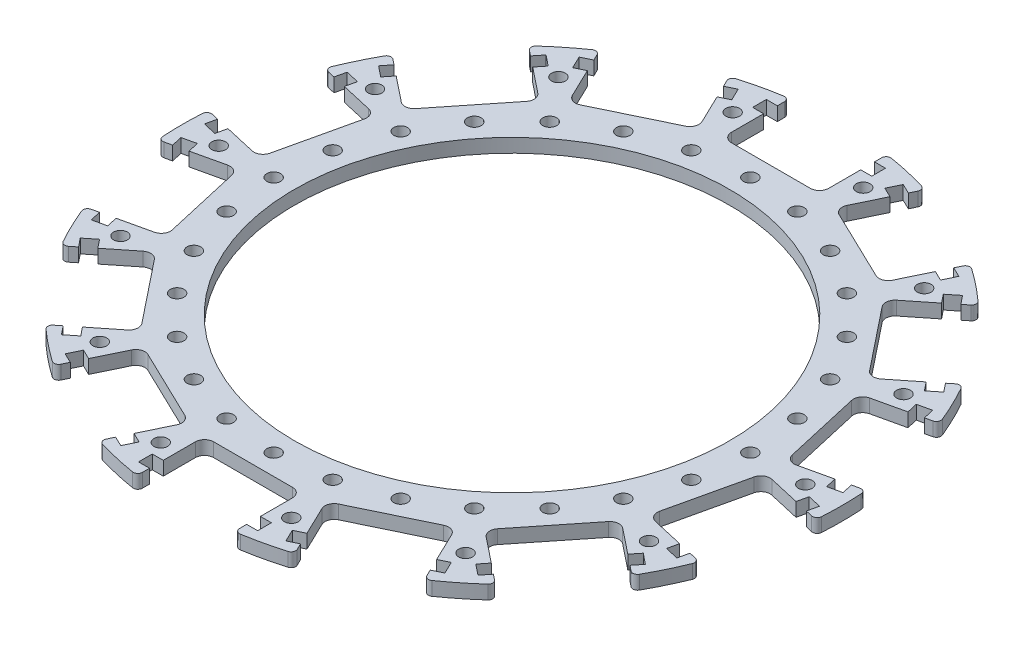
SolidWorks part; units mm, degrees
material "Thornel Mat VMA"
ref_plane "前视基准面" through (0, 0, 0) normal (0, 0, 1) x (1, 0, 0)
ref_plane "上视基准面" through (0, 0, 0) normal (0, 1, 0) x (1, 0, 0)
ref_plane "右视基准面" through (0, 0, 0) normal (1, 0, 0) x (0, 0, -1)
sketch "草图1" plane through (0, 0, 0) normal (0, 1, 0) x (1, 0, 0)
  line L0 (0, 0) -> (0, -67) construction
  line L1 (13, -67) -> (-13, -67) construction
  line L2 (-13, -68.5) -> (-13, -65.5)
  line L3 (0, -67) -> (0, -69.5129) construction
  line L4 (-10.1, -69.5129) -> (10.1, -69.5129) construction
  line L5 (-13, -68.5) -> (-10.6, -68.5)
  line L6 (-10.6, -68.5) -> (-10.6, -71.2154)
  line L7 (-13, -65.5) -> (-10.6, -65.5)
  line L8 (-10.6, -65.5) -> (-10.6, -56.5)
  line L9 (-10.6, -56.5) -> (10.6, -56.5)
  line L10 (10.6, -68.5) -> (10.6, -71.2154)
  line L11 (13, -68.5) -> (10.6, -68.5)
  line L12 (13, -68.5) -> (13, -65.5)
  line L13 (13, -65.5) -> (10.6, -65.5)
  line L14 (10.6, -65.5) -> (10.6, -56.5)
  line L15 (-34.0647, -46.3056) -> (-14.9642, -55.5039)
  line L16 (-37.9697, -54.4143) -> (-34.0647, -46.3056)
  line L17 (-40.132, -53.373) -> (-37.9697, -54.4143)
  line L18 (-41.4336, -56.0759) -> (-40.132, -53.373)
  line L19 (-41.4336, -56.0759) -> (-39.2713, -57.1172)
  line L20 (-39.2713, -57.1172) -> (-40.4495, -59.5637)
  line L21 (-20.1708, -66.3155) -> (-21.349, -68.7621)
  line L22 (-18.0084, -67.3569) -> (-20.1708, -66.3155)
  line L23 (-18.0084, -67.3569) -> (-16.7068, -64.6539)
  line L24 (-16.7068, -64.6539) -> (-18.8691, -63.6126)
  line L25 (-18.8691, -63.6126) -> (-14.9642, -55.5039)
  line L26 (-50.7825, -26.9398) -> (-37.5645, -43.5146)
  line L27 (-57.819, -32.5512) -> (-50.7825, -26.9398)
  line L28 (-59.3153, -30.6748) -> (-57.819, -32.5512)
  line L29 (-61.6608, -32.5452) -> (-59.3153, -30.6748)
  line L30 (-61.6608, -32.5452) -> (-60.1644, -34.4216)
  line L31 (-60.1644, -34.4216) -> (-62.2875, -36.1147)
  line L32 (-46.9465, -50.9965) -> (-49.0695, -52.6895)
  line L33 (-45.4501, -52.8729) -> (-46.9465, -50.9965)
  line L34 (-45.4501, -52.8729) -> (-43.1046, -51.0024)
  line L35 (-43.1046, -51.0024) -> (-44.601, -49.126)
  line L36 (-44.601, -49.126) -> (-37.5645, -43.5146)
  line L37 (-57.4421, -2.2382) -> (-52.7247, -22.9067)
  line L38 (-66.2165, -4.2409) -> (-57.4421, -2.2382)
  line L39 (-66.7506, -1.9011) -> (-66.2165, -4.2409)
  line L40 (-69.6753, -2.5686) -> (-66.7506, -1.9011)
  line L41 (-69.6753, -2.5686) -> (-69.1413, -4.9084)
  line L42 (-69.1413, -4.9084) -> (-71.7886, -5.5127)
  line L43 (-64.4238, -25.5769) -> (-67.0712, -26.1812)
  line L44 (-63.8898, -27.9167) -> (-64.4238, -25.5769)
  line L45 (-63.8898, -27.9167) -> (-60.965, -27.2492)
  line L46 (-60.965, -27.2492) -> (-61.4991, -24.9094)
  line L47 (-61.4991, -24.9094) -> (-52.7247, -22.9067)
  line L48 (-52.7247, 22.9067) -> (-57.4421, 2.2382)
  line L49 (-61.4991, 24.9094) -> (-52.7247, 22.9067)
  line L50 (-60.965, 27.2492) -> (-61.4991, 24.9094)
  line L51 (-63.8898, 27.9167) -> (-60.965, 27.2492)
  line L52 (-63.8898, 27.9167) -> (-64.4238, 25.5769)
  line L53 (-64.4238, 25.5769) -> (-67.0712, 26.1812)
  line L54 (-69.1413, 4.9084) -> (-71.7886, 5.5127)
  line L55 (-69.6753, 2.5686) -> (-69.1413, 4.9084)
  line L56 (-69.6753, 2.5686) -> (-66.7506, 1.9011)
  line L57 (-66.7506, 1.9011) -> (-66.2165, 4.2409)
  line L58 (-66.2165, 4.2409) -> (-57.4421, 2.2382)
  line L59 (-37.5645, 43.5146) -> (-50.7825, 26.9398)
  line L60 (-44.601, 49.126) -> (-37.5645, 43.5146)
  line L61 (-43.1046, 51.0024) -> (-44.601, 49.126)
  line L62 (-45.4501, 52.8729) -> (-43.1046, 51.0024)
  line L63 (-45.4501, 52.8729) -> (-46.9465, 50.9965)
  line L64 (-46.9465, 50.9965) -> (-49.0695, 52.6895)
  line L65 (-60.1644, 34.4216) -> (-62.2875, 36.1147)
  line L66 (-61.6608, 32.5452) -> (-60.1644, 34.4216)
  line L67 (-61.6608, 32.5452) -> (-59.3153, 30.6748)
  line L68 (-59.3153, 30.6748) -> (-57.819, 32.5512)
  line L69 (-57.819, 32.5512) -> (-50.7825, 26.9398)
  line L70 (-14.9642, 55.5039) -> (-34.0647, 46.3056)
  line L71 (-18.8691, 63.6126) -> (-14.9642, 55.5039)
  line L72 (-16.7068, 64.6539) -> (-18.8691, 63.6126)
  line L73 (-18.0084, 67.3569) -> (-16.7068, 64.6539)
  line L74 (-18.0084, 67.3569) -> (-20.1708, 66.3155)
  line L75 (-20.1708, 66.3155) -> (-21.349, 68.7621)
  line L76 (-39.2713, 57.1172) -> (-40.4495, 59.5637)
  line L77 (-41.4336, 56.0759) -> (-39.2713, 57.1172)
  line L78 (-41.4336, 56.0759) -> (-40.132, 53.373)
  line L79 (-40.132, 53.373) -> (-37.9697, 54.4143)
  line L80 (-37.9697, 54.4143) -> (-34.0647, 46.3056)
  line L81 (10.6, 56.5) -> (-10.6, 56.5)
  line L82 (10.6, 65.5) -> (10.6, 56.5)
  line L83 (13, 65.5) -> (10.6, 65.5)
  line L84 (13, 68.5) -> (13, 65.5)
  line L85 (13, 68.5) -> (10.6, 68.5)
  line L86 (10.6, 68.5) -> (10.6, 71.2154)
  line L87 (-10.6, 68.5) -> (-10.6, 71.2154)
  line L88 (-13, 68.5) -> (-10.6, 68.5)
  line L89 (-13, 68.5) -> (-13, 65.5)
  line L90 (-13, 65.5) -> (-10.6, 65.5)
  line L91 (-10.6, 65.5) -> (-10.6, 56.5)
  line L92 (34.0647, 46.3056) -> (14.9642, 55.5039)
  line L93 (37.9697, 54.4143) -> (34.0647, 46.3056)
  line L94 (40.132, 53.373) -> (37.9697, 54.4143)
  line L95 (41.4336, 56.0759) -> (40.132, 53.373)
  line L96 (41.4336, 56.0759) -> (39.2713, 57.1172)
  line L97 (39.2713, 57.1172) -> (40.4495, 59.5637)
  line L98 (20.1708, 66.3155) -> (21.349, 68.7621)
  line L99 (18.0084, 67.3569) -> (20.1708, 66.3155)
  line L100 (18.0084, 67.3569) -> (16.7068, 64.6539)
  line L101 (16.7068, 64.6539) -> (18.8691, 63.6126)
  line L102 (18.8691, 63.6126) -> (14.9642, 55.5039)
  line L103 (50.7825, 26.9398) -> (37.5645, 43.5146)
  line L104 (57.819, 32.5512) -> (50.7825, 26.9398)
  line L105 (59.3153, 30.6748) -> (57.819, 32.5512)
  line L106 (61.6608, 32.5452) -> (59.3153, 30.6748)
  line L107 (61.6608, 32.5452) -> (60.1644, 34.4216)
  line L108 (60.1644, 34.4216) -> (62.2875, 36.1147)
  line L109 (46.9465, 50.9965) -> (49.0695, 52.6895)
  line L110 (45.4501, 52.8729) -> (46.9465, 50.9965)
  line L111 (45.4501, 52.8729) -> (43.1046, 51.0024)
  line L112 (43.1046, 51.0024) -> (44.601, 49.126)
  line L113 (44.601, 49.126) -> (37.5645, 43.5146)
  line L114 (57.4421, 2.2382) -> (52.7247, 22.9067)
  line L115 (66.2165, 4.2409) -> (57.4421, 2.2382)
  line L116 (66.7506, 1.9011) -> (66.2165, 4.2409)
  line L117 (69.6753, 2.5686) -> (66.7506, 1.9011)
  line L118 (69.6753, 2.5686) -> (69.1413, 4.9084)
  line L119 (69.1413, 4.9084) -> (71.7886, 5.5127)
  line L120 (64.4238, 25.5769) -> (67.0712, 26.1812)
  line L121 (63.8898, 27.9167) -> (64.4238, 25.5769)
  line L122 (63.8898, 27.9167) -> (60.965, 27.2492)
  line L123 (60.965, 27.2492) -> (61.4991, 24.9094)
  line L124 (61.4991, 24.9094) -> (52.7247, 22.9067)
  line L125 (52.7247, -22.9067) -> (57.4421, -2.2382)
  line L126 (61.4991, -24.9094) -> (52.7247, -22.9067)
  line L127 (60.965, -27.2492) -> (61.4991, -24.9094)
  line L128 (63.8898, -27.9167) -> (60.965, -27.2492)
  line L129 (63.8898, -27.9167) -> (64.4238, -25.5769)
  line L130 (64.4238, -25.5769) -> (67.0712, -26.1812)
  line L131 (69.1413, -4.9084) -> (71.7886, -5.5127)
  line L132 (69.6753, -2.5686) -> (69.1413, -4.9084)
  line L133 (69.6753, -2.5686) -> (66.7506, -1.9011)
  line L134 (66.7506, -1.9011) -> (66.2165, -4.2409)
  line L135 (66.2165, -4.2409) -> (57.4421, -2.2382)
  line L136 (37.5645, -43.5146) -> (50.7825, -26.9398)
  line L137 (44.601, -49.126) -> (37.5645, -43.5146)
  line L138 (43.1046, -51.0024) -> (44.601, -49.126)
  line L139 (45.4501, -52.8729) -> (43.1046, -51.0024)
  line L140 (45.4501, -52.8729) -> (46.9465, -50.9965)
  line L141 (46.9465, -50.9965) -> (49.0695, -52.6895)
  line L142 (60.1644, -34.4216) -> (62.2875, -36.1147)
  line L143 (61.6608, -32.5452) -> (60.1644, -34.4216)
  line L144 (61.6608, -32.5452) -> (59.3153, -30.6748)
  line L145 (59.3153, -30.6748) -> (57.819, -32.5512)
  line L146 (57.819, -32.5512) -> (50.7825, -26.9398)
  line L147 (14.9642, -55.5039) -> (34.0647, -46.3056)
  line L148 (18.8691, -63.6126) -> (14.9642, -55.5039)
  line L149 (16.7068, -64.6539) -> (18.8691, -63.6126)
  line L150 (18.0084, -67.3569) -> (16.7068, -64.6539)
  line L151 (18.0084, -67.3569) -> (20.1708, -66.3155)
  line L152 (20.1708, -66.3155) -> (21.349, -68.7621)
  line L153 (39.2713, -57.1172) -> (40.4495, -59.5637)
  line L154 (41.4336, -56.0759) -> (39.2713, -57.1172)
  line L155 (41.4336, -56.0759) -> (40.132, -53.373)
  line L156 (40.132, -53.373) -> (37.9697, -54.4143)
  line L157 (37.9697, -54.4143) -> (34.0647, -46.3056)
  circle A0 centre (0, 0) radius 67 construction
  circle A1 centre (0, 0) radius 72
  point P7 (0, -67)
  point P10 (-13, -67)
  point P21 (0, -69.5129)
  point P26 (0, -56.5)
  point P185 (0, 0)
  dimension "D1" = 134
  dimension "D5" = 144
  dimension "D2" = 26
  dimension "D3" = 3
  dimension "D4" = 20.2
  dimension "D6" = 0.5
  dimension "D7" = 10.5
  dimension "D8" = 14
extrude "凸台-拉伸1" add sketch "草图1" along normal blind 3 contours L10 A1 L152 L151 L150 L149 L148 L147 L157 L156 L155 L154 L153 L141 L140 L139 L138 L137 L136 L146 L145 L144 L143 L142 L130 L129 L128 L127 L126 L125 L135 L134 L133 L132 L131 L119 L118 L117 L116 L115 L114 L124 L123 L122 L121 L120 L108
fillet "圆角1" radius 2 28 edges at (50.7825, 1.5, 26.9398) (57.4421, 1.5, 2.2382) (52.7247, 1.5, -22.9067) (37.5645, 1.5, -43.5146) (14.9642, 1.5, -55.5039) (-10.6, 1.5, -56.5) (-34.0647, 1.5, -46.3056) (-50.7825, 1.5, -26.9398) (-57.4421, 1.5, -2.2382) (-52.7247, 1.5, 22.9067) (-37.5645, 1.5, 43.5146) (-14.9642, 1.5, 55.5039) (-34.0647, 1.5, 46.3056) (-50.7825, 1.5, 26.9398) (-57.4421, 1.5, 2.2382) (-52.7247, 1.5, -22.9067) (-37.5645, 1.5, -43.5146) (-14.9642, 1.5, -55.5039) (10.6, 1.5, -56.5) (34.0647, 1.5, -46.3056) (57.4421, 1.5, -2.2382) (50.7825, 1.5, -26.9398) (52.7247, 1.5, 22.9067) (37.5645, 1.5, 43.5146) (34.0647, 1.5, 46.3056) (14.9642, 1.5, 55.5039) (10.6, 1.5, 56.5) (-10.6, 1.5, 56.5)
fillet "圆角2" radius 1 28 edges at (40.4495, 1.5, 59.5637) (10.6, 1.5, 71.2154) (62.2875, 1.5, 36.1147) (71.7886, 1.5, 5.5127) (67.0712, 1.5, -26.1812) (49.0695, 1.5, -52.6895) (21.349, 1.5, -68.7621) (-10.6, 1.5, -71.2154) (-40.4495, 1.5, -59.5637) (-62.2875, 1.5, -36.1147) (-71.7886, 1.5, -5.5127) (-67.0712, 1.5, 26.1812) (-21.349, 1.5, 68.7621) (-49.0695, 1.5, 52.6895) (-40.4495, 1.5, 59.5637) (-62.2875, 1.5, 36.1147) (-71.7886, 1.5, 5.5127) (-67.0712, 1.5, -26.1812) (-49.0695, 1.5, -52.6895) (-21.349, 1.5, -68.7621) (10.6, 1.5, -71.2154) (40.4495, 1.5, -59.5637) (62.2875, 1.5, -36.1147) (71.7886, 1.5, -5.5127) (67.0712, 1.5, 26.1812) (49.0695, 1.5, 52.6895) (21.349, 1.5, 68.7621) (-10.6, 1.5, 71.2154)
sketch "草图2" plane through (0, 0, 0) normal (0, 1, 0) x (1, 0, 0)
  line L0 (64, 0) -> (0, 0) construction
  circle A0 centre (64, 0) radius 1.5
  circle A1 centre (57.662, -27.7686) radius 1.5
  circle A2 centre (39.9033, -50.0372) radius 1.5
  circle A3 centre (14.2413, -62.3954) radius 1.5
  circle A4 centre (-14.2413, -62.3954) radius 1.5
  circle A5 centre (-39.9033, -50.0372) radius 1.5
  circle A6 centre (-57.662, -27.7686) radius 1.5
  circle A7 centre (-64, 0) radius 1.5
  circle A8 centre (-57.662, 27.7686) radius 1.5
  circle A9 centre (-39.9033, 50.0372) radius 1.5
  circle A10 centre (-14.2413, 62.3954) radius 1.5
  circle A11 centre (14.2413, 62.3954) radius 1.5
  circle A12 centre (39.9033, 50.0372) radius 1.5
  circle A13 centre (57.662, 27.7686) radius 1.5
  point P32 (0, 0)
  dimension "D1" = 3
  dimension "D2" = 64
  dimension "D3" = 14
extrude "切除-拉伸1" cut sketch "草图2" along normal blind 11
sketch "草图3" plane through (0, 0, 0) normal (0, 1, 0) x (1, 0, 0)
  line L0 (0, -56.5) -> (0, -52.5) construction
  line L1 (-8.6, -56.5) -> (8.6, -56.5) construction
  circle A0 centre (0, 0) radius 9 construction
  circle A1 centre (0, 0) radius 28 construction
  circle A2 centre (0, 0) radius 52.5
  dimension "D1" = 18
  dimension "D2" = 56
  dimension "D3" = 4
extrude "切除-拉伸2" cut sketch "草图3" along normal blind 11 contours A0 | A2 A1
sketch "草图4" plane through (0, 3, 0) normal (0, 1, 0) x (1, 0, 0)
  circle A0 centre (0, 0) radius 47.5
  circle A1 centre (0, 0) radius 52.5
  dimension "D1" = 95
  dimension "D2" = 105
extrude "凸台-拉伸2" add sketch "草图4" against normal blind 3
sketch "草图5" plane through (0, 3, 0) normal (0, 1, 0) x (1, 0, 0)
  circle A0 centre (0, 0) radius 52 construction
  circle A1 centre (0, 52) radius 1.5
  circle A2 centre (11.5711, 50.6963) radius 1.5
  circle A3 centre (22.562, 46.8504) radius 1.5
  circle A4 centre (32.4215, 40.6552) radius 1.5
  circle A5 centre (40.6552, 32.4215) radius 1.5
  circle A6 centre (46.8504, 22.562) radius 1.5
  circle A7 centre (50.6963, 11.5711) radius 1.5
  circle A8 centre (52, 0) radius 1.5
  circle A9 centre (50.6963, -11.5711) radius 1.5
  circle A10 centre (46.8504, -22.562) radius 1.5
  circle A11 centre (40.6552, -32.4215) radius 1.5
  circle A12 centre (32.4215, -40.6552) radius 1.5
  circle A13 centre (22.562, -46.8504) radius 1.5
  circle A14 centre (11.5711, -50.6963) radius 1.5
  circle A15 centre (0, -52) radius 1.5
  circle A16 centre (-11.5711, -50.6963) radius 1.5
  circle A17 centre (-22.562, -46.8504) radius 1.5
  circle A18 centre (-32.4215, -40.6552) radius 1.5
  circle A19 centre (-40.6552, -32.4215) radius 1.5
  circle A20 centre (-46.8504, -22.562) radius 1.5
  circle A21 centre (-50.6963, -11.5711) radius 1.5
  circle A22 centre (-52, 0) radius 1.5
  circle A23 centre (-50.6963, 11.5711) radius 1.5
  circle A24 centre (-46.8504, 22.562) radius 1.5
  circle A25 centre (-40.6552, 32.4215) radius 1.5
  circle A26 centre (-32.4215, 40.6552) radius 1.5
  circle A27 centre (-22.562, 46.8504) radius 1.5
  circle A28 centre (-11.5711, 50.6963) radius 1.5
  point P6 (-27.8069, 15.5586)
  point P7 (-19.5972, 40.32)
  point P61 (0, 0)
  point P62 (0, 0)
  dimension "D1" = 104
  dimension "D2" = 3
  dimension "D3" = 28
extrude "切除-拉伸3" cut sketch "草图5" against normal blind 3
